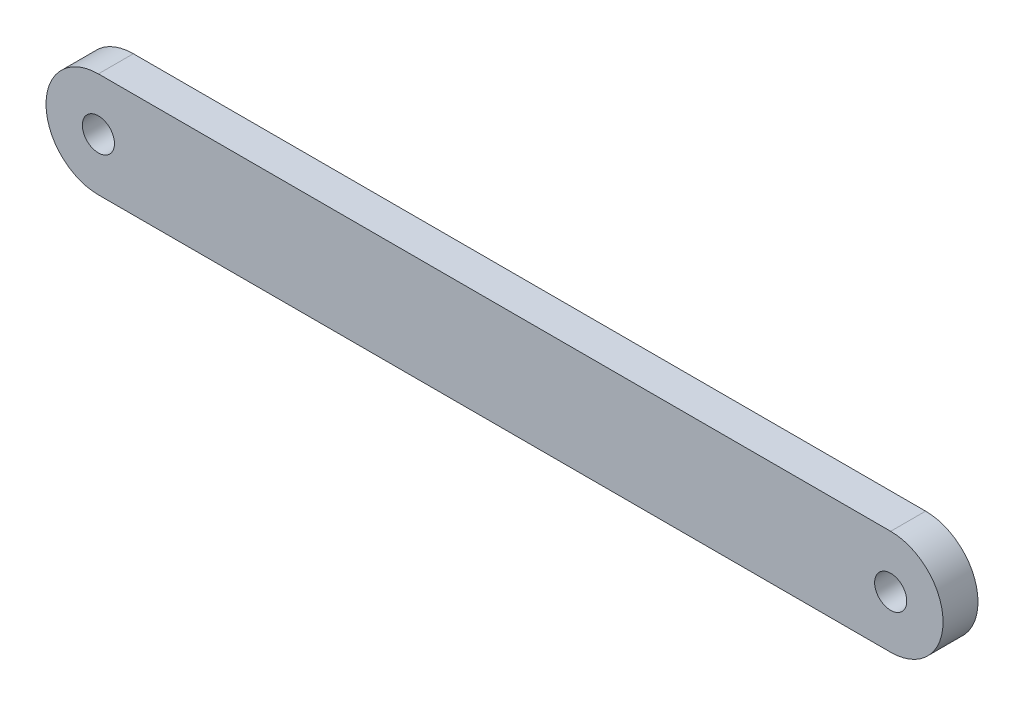
SolidWorks part; units mm, degrees
ref_plane "前视基准面" through (0, 0, 0) normal (0, 0, 1) x (1, 0, 0)
ref_plane "上视基准面" through (0, 0, 0) normal (0, 1, 0) x (1, 0, 0)
ref_plane "右视基准面" through (0, 0, 0) normal (1, 0, 0) x (0, 0, -1)
other "Configuration Table"
sketch "草图1" plane through (0, 0, 0) normal (0, 0, 1) x (1, 0, 0)
  line L1 (-56.7, 7.5) -> (56.7, 7.5)
  line L3 (-56.7, -7.5) -> (56.7, -7.5)
  line L5 (-56.7, 7.5) -> (56.7, -7.5) construction
  line L6 (-56.7, -7.5) -> (56.7, 7.5) construction
  arc A0 (-56.7, 7.5) -> (-56.7, -7.5) centre (-56.7, 0) ccw
  arc A1 (56.7, 7.5) -> (56.7, -7.5) centre (56.7, 0) cw
  circle A2 centre (-56.7, 0) radius 2.3
  circle A3 centre (56.7, 0) radius 2.3
  point P0 (0, 0)
  dimension "D1" = 4.6
  dimension "D2" = 4.6
  dimension "D3" = 113.4
  dimension "D4" = 15
extrude "凸台-拉伸1" add sketch "草图1" along normal blind 5
equation "\"fi\"=4.6"
equation "\"D1@草图1\"=\"fi\""
equation "\"D2@草图1\"=\"fi\""
equation "\"b0\"=75.6"
equation "\"b1\"= \"b0\" * 3 / 2"
equation "\"D3@草图1\"=\"b1\""
equation "\"width\"=15"
equation "\"D4@草图1\"=\"width\""
equation "\"depth\"=5"
equation "\"D1@凸台-拉伸1\"=\"depth\""
equation "\"b2\"= \"b0\" * 6 / 2"
equation "\"b3\"= \"b0\" * 4 / 2"
equation "\"b4\"= \"b0\" * 7 / 2"
equation "\"angle\"= 90度"
